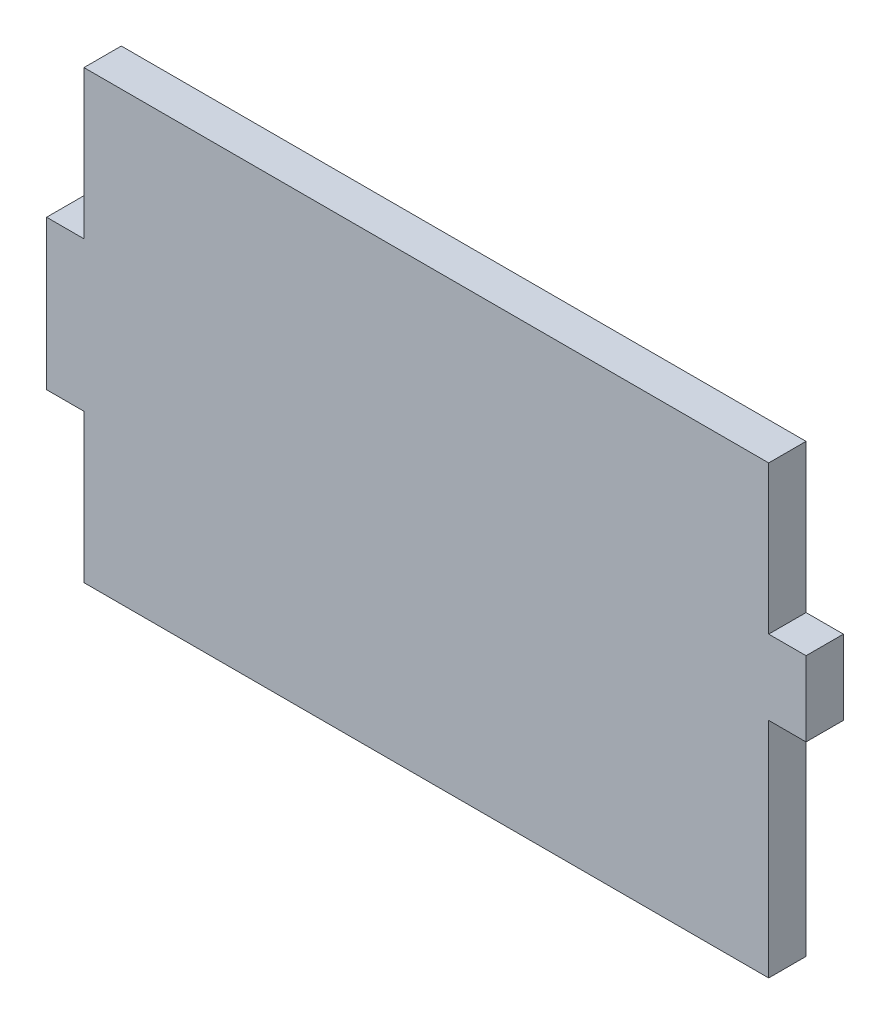
SolidWorks part; units mm, degrees
ref_plane "Přední rovina" through (0, 0, 0) normal (0, 0, 1) x (1, 0, 0)
ref_plane "Horní rovina" through (0, 0, 0) normal (0, 1, 0) x (1, 0, 0)
ref_plane "Pravá rovina" through (0, 0, 0) normal (1, 0, 0) x (0, 0, -1)
sketch "Skica1" plane through (0, 0, 0) normal (0, 0, 1) x (1, 0, 0)
  line L0 (55, -17.91) -> (55, -35.83)
  line L1 (0, 0) -> (55, 0)
  line L2 (0, 0) -> (0, -11.91)
  line L3 (0, -35.83) -> (55, -35.83)
  line L4 (55, 0) -> (55, -11.91)
  line L5 (0, -11.91) -> (-3, -11.91)
  line L6 (0, -23.91) -> (-3, -23.91)
  line L7 (-3, -11.91) -> (-3, -23.91)
  line L8 (55, -11.91) -> (58, -11.91)
  line L9 (55, -17.91) -> (58, -17.91)
  line L10 (58, -11.91) -> (58, -17.91)
  line L11 (0, -23.91) -> (0, -35.83)
  dimension "D1" = 55
  dimension "D2" = 35.83
  dimension "D3" = 11.91
  dimension "D4" = 0
  dimension "D5" = 6
  dimension "D6" = 12
  dimension "D7" = 3
  dimension "D8" = 3
extrude "Přidat vysunutím1" add sketch "Skica1" along normal blind 3
